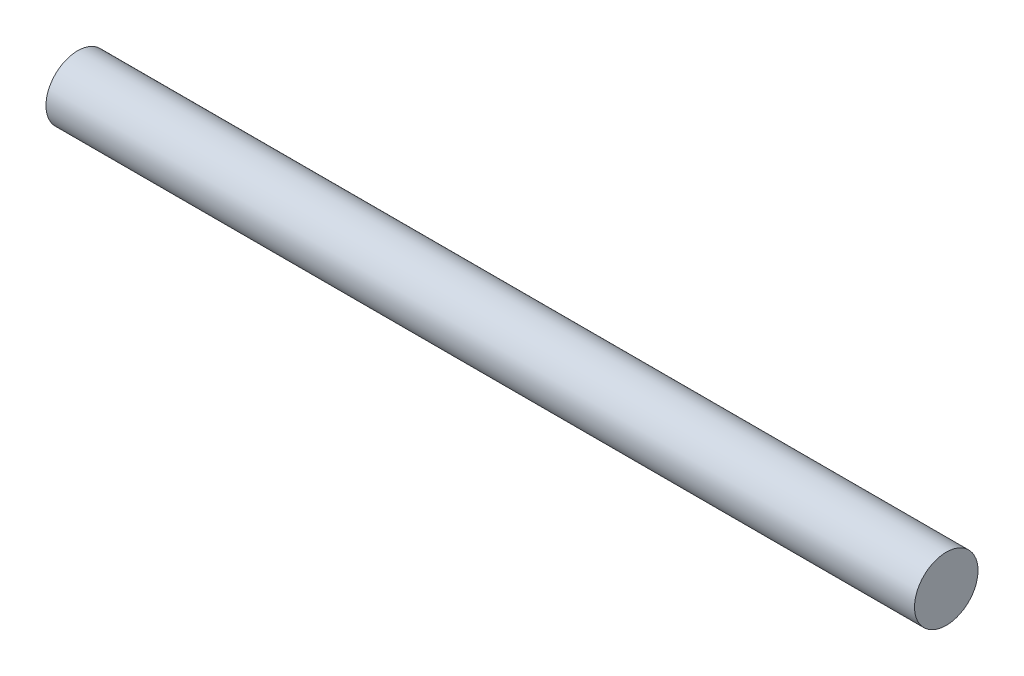
SolidWorks part; units mm, degrees
material "Custom Plastic"
ref_plane "Front Plane" through (0, 0, 0) normal (0, 0, 1) x (1, 0, 0)
ref_plane "Top Plane" through (0, 0, 0) normal (0, 1, 0) x (1, 0, 0)
ref_plane "Right Plane" through (0, 0, 0) normal (1, 0, 0) x (0, 0, -1)
sketch "Sketch1" plane through (0, 0, 0) normal (1, 0, 0) x (0, 0, -1)
  circle A0 centre (0, 0) radius 11.11
  dimension "D1" = 22.22
extrude "Boss-Extrude1" add sketch "Sketch1" along normal blind 304
hole_wizard "Ø3.0 (3) Diameter Hole2" positions "Sketch7" profile "Sketch6" hole size "Ø3.0" standard "ANSI Metric"
sketch "Sketch7" plane through (0, 0, 0) normal (-1, 0, 0) x (0, 0, 1)
  point P0 (0, 5.3)
  dimension "D1" = 5.3
sketch "Sketch6" plane through (0, 5.3, 0) normal (0, 1, 0) x (0, 0, 1)
  line L0 (0, 0) -> (0, 11.9013)
  line L1 (0, 11.9013) -> (1.5, 11)
  line L2 (1.5, 11) -> (1.5, 0)
  line L5 (1.5, 0) -> (0, 0)
  line L10 (0, 11.9013) -> (-1.5, 11) construction
  line L11 (0, -6.35) -> (0, 107.95) construction
  dimension "Hole Dia." = 3
  dimension "Hole Depth" = 11
  dimension "Drill Angle" = 118
ref_plane "Plane1" through (0, 11.11, 0) normal (0, 1, 0) x (1, 0, 0)
ref_plane "Plane2" through (0, -5.555, 9.6215) normal (0, -0.5, 0.866) x (-1, 0, 0)
ref_plane "Plane3" through (0, -5.555, -9.6215) normal (0, -0.5, -0.866) x (-1, 0, 0)
